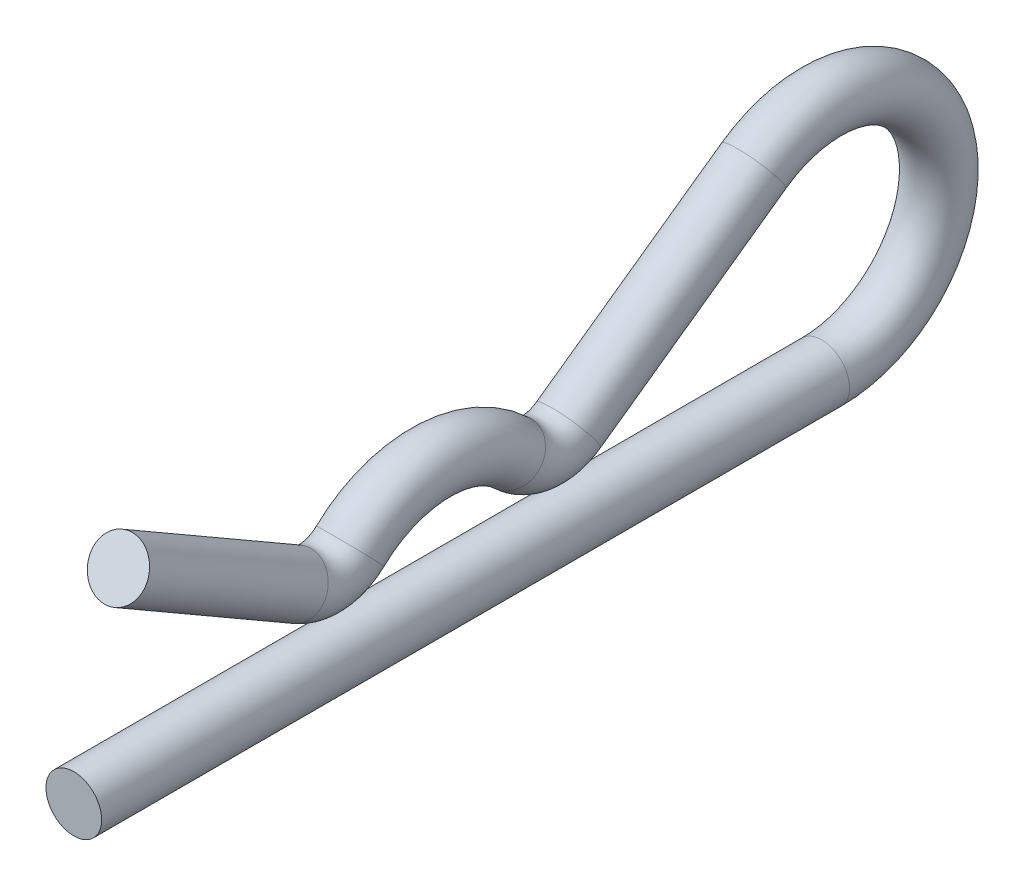
SolidWorks part; units mm, degrees
material "Alloy Steel"
ref_plane "Front" through (0, 0, 0) normal (0, 0, 1) x (1, 0, 0)
ref_plane "Top" through (0, 0, 0) normal (0, 1, 0) x (1, 0, 0)
ref_plane "Right" through (0, 0, 0) normal (1, 0, 0) x (0, 0, -1)
sketch "Sketch1" plane through (0, 0, 0) normal (1, 0, 0) x (0, 0, -1)
  line L0 (-15.875, -4.1656) -> (10.7188, -4.1656) construction
  line L1 (-7.1431, 0) -> (0.7931, 0) construction
  line L2 (15.875, -4.1656) -> (15.875, 0) construction
  line L3 (15.875, 0) -> (14.8844, 0) construction
  line L4 (-15.875, -4.1656) -> (-15.875, -3.175) construction
  line L5 (15.875, -4.1656) -> (-15.875, -4.1656) construction
  line L6 (-7.9369, -1.3748) -> (-14.2875, 2.2917) construction
  line L7 (-3.175, 0) -> (-3.175, -4.1656) construction
  line L8 (-15.875, -4.1656) -> (-15.875, -5.1562) construction
  line L9 (15.875, -4.1656) -> (15.875, 4.1656) construction
  line L10 (15.875, 4.1656) -> (-15.875, 4.1656) construction
  line L11 (-15.875, 4.1656) -> (-15.875, -4.1656) construction
  line L12 (0, 4.1656) -> (0, -4.1656) construction
  line L13 (8.3043, 3.3945) -> (1.7133, -1.2936) construction
  circle A0 centre (10.7188, 0) radius 3.175 construction
  arc A1 (-0.3018, -1.1494) -> (-6.0482, -1.1494) centre (-3.175, -4.1656) ccw construction
  arc A6 (-6.0482, -1.1494) -> (-7.9369, -1.3748) centre (-7.1431, 0) cw construction
  arc A8 (1.7133, -1.2936) -> (-0.3018, -1.1494) centre (0.7931, 0) cw construction
  arc A9 (10.7188, -4.1656) -> (8.3043, 3.3945) centre (10.7188, 0) ccw construction
  point P2 (0, 0)
  dimension "D1" = 1.5875
  dimension "EyeID" = 6.35
  dimension "D2" = 12.7
  dimension "D5" = 1.5875
  dimension "D9" = 30
  dimension "D11" = 0.9906
  dimension "D3" = 0.9906
  dimension "Length" = 31.75
  dimension "Wire OD" = 1.9812
ref_plane "Plane1" through (0, 0, 15.875) normal (0, 0, 1) x (1, 0, 0)
sketch "Sketch3" plane through (0, 0, 15.875) normal (0, 0, 1) x (1, 0, 0)
  circle A0 centre (0, -4.1656) radius 0.9906
sketch "Sketch4" plane through (0, 0, 0) normal (1, 0, 0) x (0, 0, -1)
  line L0 (-7.9369, -1.3748) -> (-14.2875, 2.2917) construction
  line L1 (8.3043, 3.3945) -> (1.7133, -1.2936) construction
  line L2 (-15.875, -4.1656) -> (10.7188, -4.1656) construction
  line L3 (-7.9369, -1.3748) -> (-14.2875, 2.2917)
  line L4 (8.3043, 3.3945) -> (1.7133, -1.2936)
  line L5 (-15.875, -4.1656) -> (10.7188, -4.1656)
  arc A0 (-7.9369, -1.3748) -> (-6.0482, -1.1494) centre (-7.1431, 0) ccw construction
  arc A1 (-0.3018, -1.1494) -> (-6.0482, -1.1494) centre (-3.175, -4.1656) ccw construction
  arc A2 (-0.3018, -1.1494) -> (1.7133, -1.2936) centre (0.7931, 0) ccw construction
  arc A3 (10.7188, -4.1656) -> (8.3043, 3.3945) centre (10.7188, 0) ccw construction
  arc A4 (-7.9369, -1.3748) -> (-6.0482, -1.1494) centre (-7.1431, 0) ccw
  arc A5 (-0.3018, -1.1494) -> (-6.0482, -1.1494) centre (-3.175, -4.1656) ccw
  arc A6 (-0.3018, -1.1494) -> (1.7133, -1.2936) centre (0.7931, 0) ccw
  arc A7 (10.7188, -4.1656) -> (8.3043, 3.3945) centre (10.7188, 0) ccw
sweep "Sweep1" add profiles "Sketch3" path "Sketch4"
equation "\"D11@Sketch1\" = \"Wire OD@Sketch1\" / 2"
equation "\"D1@Sketch1\" = \"EyeID@Sketch1\" / 4"
equation "\"D3@Sketch1\" = \"D11@Sketch1\""
equation "\"D2@Sketch1\" =  ( \"Length@Sketch1\" - \"EyeID@Sketch1\" )  / 2"
equation "\"D5@Sketch1\" = \"Length@Sketch1\" * .05"
